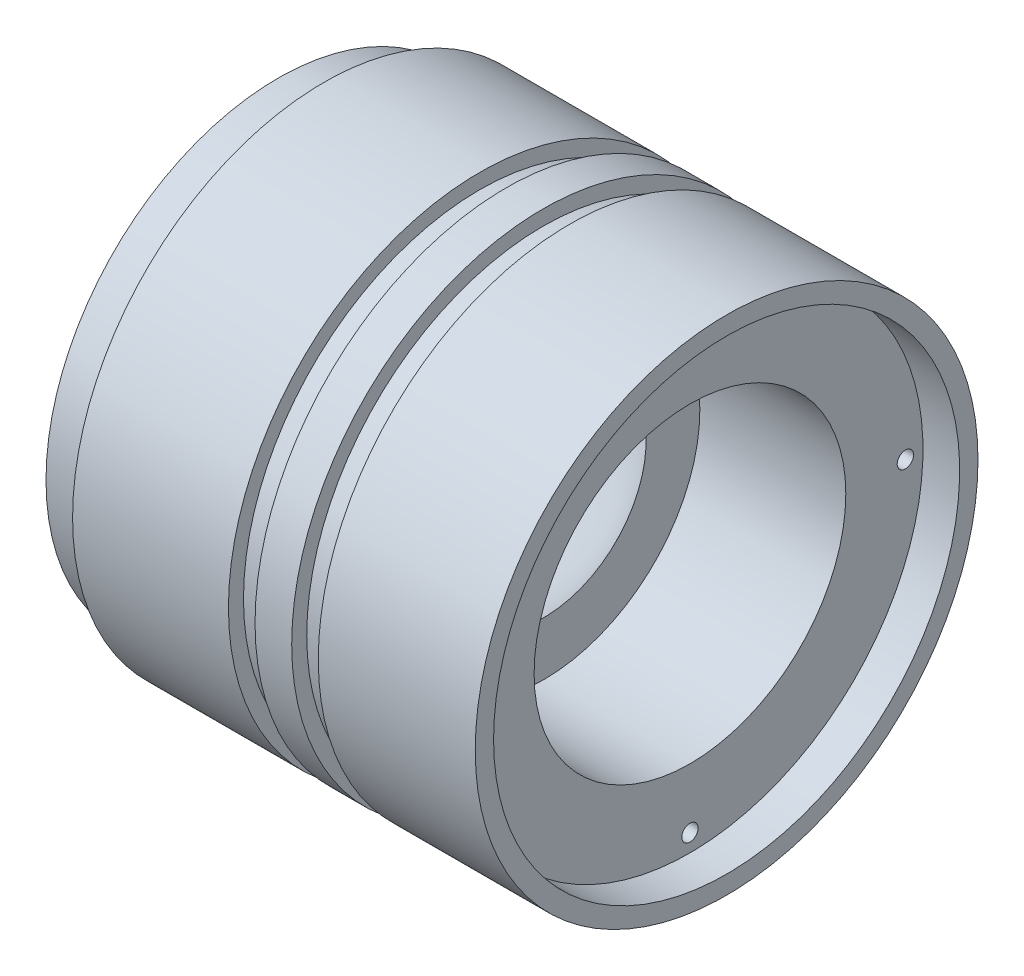
SolidWorks part; units mm, degrees
material "AISI 304"
ref_plane "Front Plane" through (0, 0, 0) normal (0, 0, 1) x (1, 0, 0)
ref_plane "Top Plane" through (0, 0, 0) normal (0, 1, 0) x (1, 0, 0)
ref_plane "Right Plane" through (0, 0, 0) normal (1, 0, 0) x (0, 0, -1)
ref_axis "Axis1" through (-14.407, 0, 0) along (1, 0, 0)
sketch "Sketch1" plane through (0, 0, 0) normal (0, 0, 1) x (1, 0, 0)
  line L0 (0, -55) -> (0, 55) construction
  line L1 (0, 34.8234) -> (101.6, 34.8234)
  line L2 (0, 34.8234) -> (0, 0)
  line L3 (0, 0) -> (101.6, 0)
  line L4 (101.6, 34.8234) -> (101.6, 0)
  line L5 (55, 0) -> (-55, 0) construction
  dimension "D1" = 34.8234
  dimension "D2" = 101.6
revolve "Revolve1" add sketch "Sketch1" angle 360 about axis through (-14.407, 0, 0) along (1, 0, 0)
sketch "Sketch2" plane through (0, 0, 0) normal (0, 0, 1) x (1, 0, 0)
  line L0 (0, 28.4734) -> (10.16, 28.4734)
  line L1 (0, -38.3057) -> (0, 38.3057) construction
  line L2 (0, 28.4734) -> (0, 0)
  line L3 (101.6, 24.9936) -> (101.6, 0)
  line L5 (101.6, -34.8234) -> (101.6, 34.8234) construction
  line L7 (101.6, 0) -> (0, 0)
  line L8 (48.1206, 8.8004) -> (59.2205, 13.9763) construction
  line L9 (101.6, 24.9936) -> (122.8287, 29.12) construction
  arc A0 (10.16, 28.4734) -> (36.83, 14.151) centre (10.16, -3.5192) cw
  arc A1 (36.83, 14.151) -> (46.482, 8.5) centre (47.4171, 21.1655) ccw
  arc A2 (46.482, 8.5) -> (48.1206, 8.8004) centre (46.7251, 11.793) ccw
  parabola Q0 (101.6, 24.9936) -> (48.1206, 8.8004) focus (30.6468, -36.2749) apex (8.7156, -28.8042)
  dimension "D3" = 3.302
  dimension "D4" = 12.7
  dimension "D1" = 28.4734
  dimension "D2" = 10.16
  dimension "D5" = 25
  dimension "D6" = 26.67
  dimension "D7" = 8.5
  dimension "D8" = 11
  dimension "D9" = 46.482
  dimension "D10" = 24.9936
revolve "Cut-Revolve1" cut sketch "Sketch2" angle 360 about axis through (-14.407, 0, 0) along (1, 0, 0)
sketch "Sketch3" plane through (0, 0, 0) normal (0, 0, 1) x (1, 0, 0)
  line L0 (0, -38.3057) -> (0, 38.3057) construction
  line L1 (0, 34.8234) -> (6.35, 34.8234)
  line L2 (0, 34.8234) -> (0, 32.1564)
  line L3 (0, 32.1564) -> (6.35, 32.1564)
  line L4 (6.35, 34.8234) -> (6.35, 32.1564)
  line L5 (-14.407, 0) -> (111.4249, 0) construction
  dimension "D1" = 6.35
  dimension "D2" = 32.1564
  dimension "D3" = 34.8234
revolve "Cut-Revolve2" cut sketch "Sketch3" angle 360 about axis through (-14.407, 0, 0) along (1, 0, 0)
sketch "Sketch4" plane through (0, 0, 0) normal (0, 0, 1) x (1, 0, 0)
  line L0 (101.6, -34.8234) -> (101.6, 34.8234) construction
  line L1 (101.6, 25.8064) -> (63.5, 25.8064)
  line L2 (101.6, 25.8064) -> (101.6, 34.8234)
  line L3 (101.6, 34.8234) -> (63.5, 34.8234)
  line L4 (63.5, 25.8064) -> (63.5, 34.8234)
  line L5 (-14.407, 0) -> (111.4249, 0) construction
  dimension "D1" = 9.017
  dimension "D2" = 38.1
  dimension "D3" = 34.8234
revolve "Cut-Revolve3" cut sketch "Sketch4" angle 360 about axis through (-14.407, 0, 0) along (1, 0, 0)
sketch "Sketch5" plane through (0, 0, 0) normal (0, 0, 1) x (1, 0, 0)
  line L0 (36.83, 0) -> (36.83, 21.59)
  line L1 (38.3057, 0) -> (-38.3057, 0) construction
  line L2 (36.83, 21.59) -> (57.0484, 21.59)
  line L3 (57.0484, 21.59) -> (57.0484, 32.2834)
  line L4 (57.0484, 32.2834) -> (62.1284, 32.2834)
  line L5 (62.1284, 32.2834) -> (62.1284, 34.8234)
  line L6 (36.83, 0) -> (101.6, 0)
  line L7 (101.6, 0) -> (101.6, 34.8234)
  line L8 (101.6, 34.8234) -> (62.1284, 34.8234)
  line L9 (0, -38.3057) -> (0, 38.3057) construction
  line L10 (-14.407, 0) -> (111.4249, 0) construction
  line L11 (101.6, -24.9936) -> (101.6, 24.9936) construction
  dimension "D1" = 36.83
  dimension "D2" = 21.59
  dimension "D3" = 20.2184
  dimension "D4" = 2.54
  dimension "D5" = 5.08
  dimension "D6" = 34.8234
revolve "Cut-Revolve4" cut sketch "Sketch5" angle 360 about axis through (-14.407, 0, 0) along (1, 0, 0)
hole_wizard "#4-40 Tapped Hole1" positions "Sketch6" profile "Sketch7" tap size "#4-40" standard "ANSI Inch"
sketch "Sketch6" plane through (57.0484, 0, 0) normal (1, 0, 0) x (0, 0, -1)
  line L2 (38.3057, 0) -> (-38.3057, 0) construction
  point P0 (0, 29.845)
  dimension "D1" = 29.845
sketch "Sketch7" plane through (57.0484, 29.845, 0) normal (0, 1, 0) x (0, 0, -1)
  line L0 (0, 0) -> (0, 10.8392)
  line L1 (0, 10.8392) -> (1.1303, 10.16)
  line L2 (1.1303, 10.16) -> (1.1303, 0)
  line L5 (1.1303, 0) -> (0, 0)
  line L10 (0, 10.8392) -> (-1.1303, 10.16) construction
  line L11 (0, -6.35) -> (0, 107.95) construction
  dimension "Tap Drill Dia." = 2.2606
  dimension "Tap Drill Depth" = 10.16
  dimension "Drill Angle" = 118
cosmetic thread "Hole Thread1" parameters "D1"=8.89, "D2"=2.8448
pattern_circular "CirPattern1" count 4 over 360 about axis through (0, 0, 0) along (1, 0, 0) of "#4-40 Tapped Hole1"
sketch "Sketch8" plane through (0, 0, 0) normal (0, 0, 1) x (1, 0, 0)
  line L0 (34.2265, 0) -> (-34.2265, 0) construction
  line L1 (27.94, 34.8234) -> (31.623, 34.8234)
  line L2 (27.94, 34.8234) -> (27.94, 32.7406)
  line L3 (27.94, 32.7406) -> (31.623, 32.7406)
  line L4 (31.623, 34.8234) -> (31.623, 32.7406)
  line L5 (36.703, 34.8234) -> (40.386, 34.8234)
  line L6 (36.703, 34.8234) -> (36.703, 32.7406)
  line L7 (36.703, 32.7406) -> (40.386, 32.7406)
  line L8 (40.386, 34.8234) -> (40.386, 32.7406)
  line L9 (0, -38.3057) -> (0, 38.3057) construction
  point P10 (27.94, 33.782)
  dimension "D1" = 3.683
  dimension "D2" = 5.08
  dimension "D3" = 3.683
  dimension "D4" = 32.7406
  dimension "D5" = 34.8234
  dimension "D6" = 27.94
revolve "Cut-Revolve5" cut sketch "Sketch8" angle 360 about axis through (-14.407, 0, 0) along (1, 0, 0)
sketch "Sketch9" plane through (0, 0, 0) normal (0, 0, 1) x (1, 0, 0)
  line L0 (57.0484, -21.59) -> (57.0484, 21.59) construction
  line L1 (57.0484, -21.59) -> (57.0484, 21.59) construction
  line L2 (57.0484, 21.59) -> (24.3582, 21.59) construction
equation "\"throat_radius\"= 8.5mm"
equation "\"diverg_circle_rad\"= 0.382 * \"throat_radius\""
equation "\"converg_circle_rad\"= 1.5 * \"throat_radius\""
